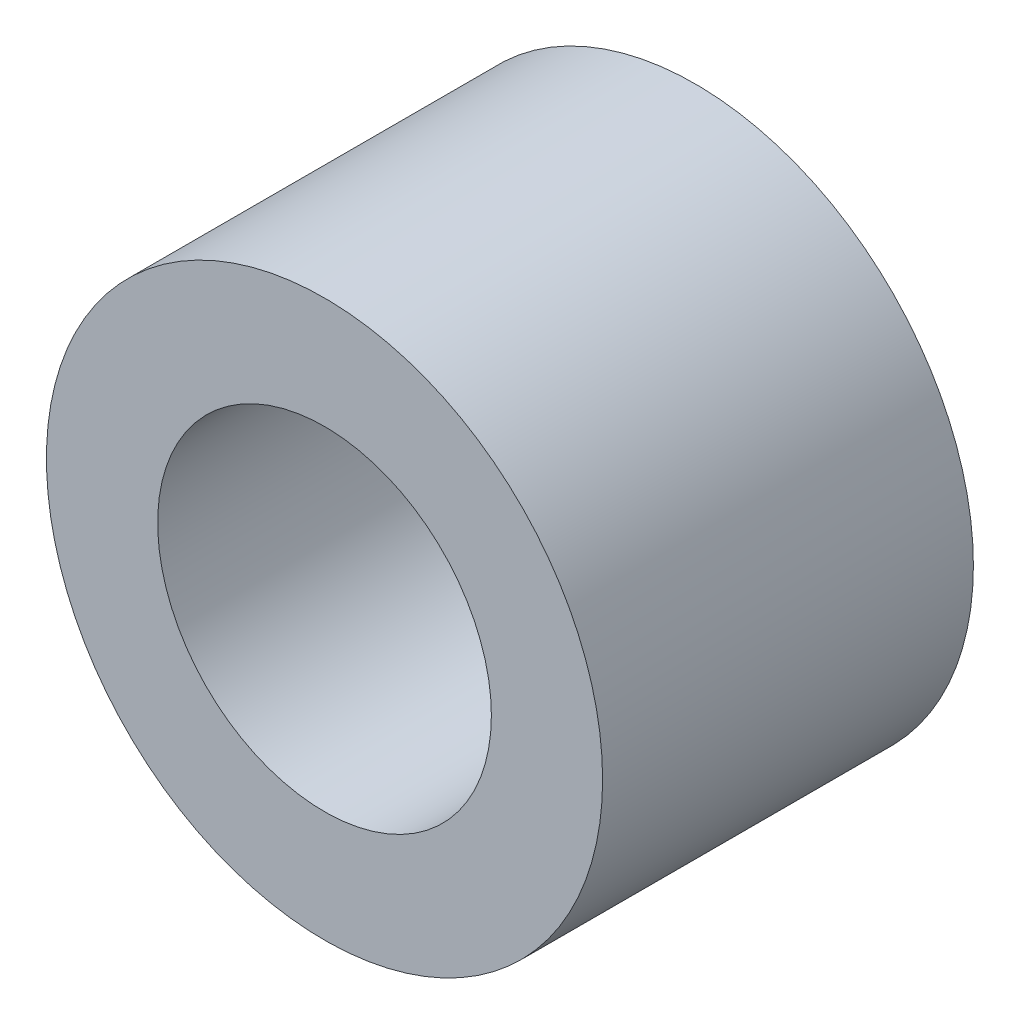
SolidWorks part; units mm, degrees
material "ABS"
ref_plane "Front Plane" through (0, 0, 0) normal (0, 0, 1) x (1, 0, 0)
ref_plane "Top Plane" through (0, 0, 0) normal (0, 1, 0) x (1, 0, 0)
ref_plane "Right Plane" through (0, 0, 0) normal (1, 0, 0) x (0, 0, -1)
sketch "Sketch1" plane through (0, 0, 0) normal (0, 0, 1) x (1, 0, 0)
  circle A0 centre (0, 0) radius 4.5
  circle A1 centre (0, 0) radius 7.5
  dimension "D1" = 15
  dimension "D2" = 9
extrude "Boss-Extrude1" add sketch "Sketch1" along normal blind 10
